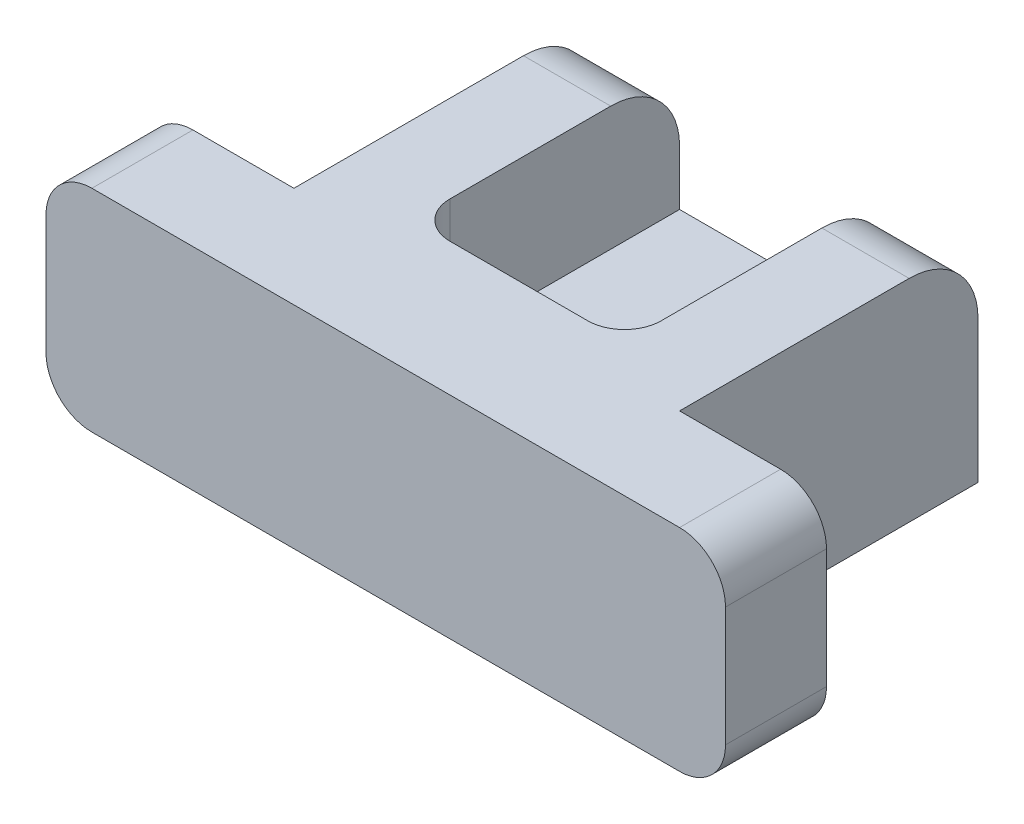
SolidWorks part; units mm, degrees
ref_plane "Ön Düzlem" through (0, 0, 0) normal (0, 0, 1) x (1, 0, 0)
ref_plane "Üst Düzlem" through (0, 0, 0) normal (0, 1, 0) x (1, 0, 0)
ref_plane "Sağ Düzlem" through (0, 0, 0) normal (1, 0, 0) x (0, 0, -1)
sketch "Çizim1" plane through (0, 0, 0) normal (0, 0, 1) x (1, 0, 0)
  line L0 (-640, 460) -> (640, 460)
  line L1 (740, 360) -> (740, 100)
  line L2 (640, 0) -> (-640, 0)
  line L3 (0, 460) -> (0, 0) construction
  line L4 (-740, 360) -> (-740, 100)
  arc A0 (740, 360) -> (640, 460) centre (640, 360) ccw
  arc A1 (740, 100) -> (640, 0) centre (640, 100) cw
  arc A2 (-740, 100) -> (-640, 0) centre (-640, 100) ccw
  arc A3 (-740, 360) -> (-640, 460) centre (-640, 360) cw
  point P7 (740, 460)
  point P10 (740, 0)
  point P17 (-740, 0)
  point P18 (-740, 460)
  dimension "D3" = 100
  dimension "D4" = 100
  dimension "D1" = 460
  dimension "D2" = 740
extrude "Yükseklik-Ekstrüzyon1" add sketch "Çizim1" along normal blind 220
sketch "Çizim2" plane through (0, 460, 0) normal (0, 1, 0) x (1, 0, 0)
  line L0 (0, 0) -> (0, 650) construction
  line L1 (-420, 650) -> (420, 650)
  line L2 (420, 650) -> (420, 0)
  line L3 (640, 0) -> (-640, 0) construction
  line L4 (-420, 650) -> (-420, 0)
  line L5 (-420, 0) -> (420, 0)
  point P11 (0, 650)
  dimension "D1" = 420
  dimension "D2" = 650
  dimension "D3" = 650
extrude "Yükseklik-Ekstrüzyon2" add sketch "Çizim2" against normal up to vertex (460 mm away) up to point (0, 0, 0)
sketch "Çizim3" plane through (0, 460, 0) normal (0, 1, 0) x (1, 0, 0)
  line L0 (0, 650) -> (0, -211.2455) construction
  line L1 (420, 650) -> (-420, 650) construction
  line L2 (420, 650) -> (230, 650)
  line L3 (230, 650) -> (230, 150)
  line L4 (150, 70) -> (-150, 70)
  line L5 (-230, 650) -> (-230, 150)
  line L6 (-230, 650) -> (230, 650)
  arc A0 (150, 70) -> (230, 150) centre (150, 150) ccw
  arc A1 (-150, 70) -> (-230, 150) centre (-150, 150) cw
  point P12 (230, 70)
  point P16 (0, 70)
  point P17 (-230, 70)
  line M3 (420, 650) -> (-420, 650)
  dimension "D3" = 80
  dimension "D1" = 190
  dimension "D2" = 580
extrude "Kes-Ekstrüzyon1" cut sketch "Çizim3" against normal blind 270 contours L0 L6 L5 A1 L4 | L0 L4 A0 L3 M3
fillet "Radyus2" radius 150 1 edges at (-325, 460, -650)
fillet "Radyus3" radius 150 1 edges at (325, 460, -650)
